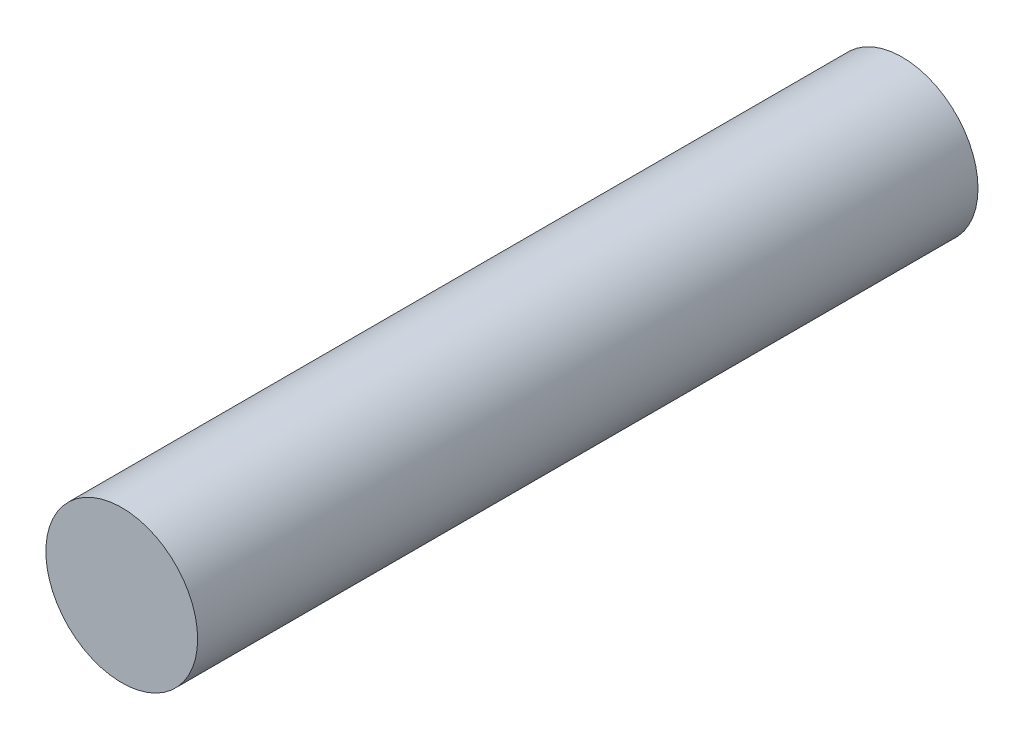
SolidWorks part; units mm, degrees
ref_plane "Plan de face" through (0, 0, 0) normal (0, 0, 1) x (1, 0, 0)
ref_plane "Plan de dessus" through (0, 0, 0) normal (0, 1, 0) x (1, 0, 0)
ref_plane "Plan de droite" through (0, 0, 0) normal (1, 0, 0) x (0, 0, -1)
sketch "Esquisse2" plane through (0, 0, 0) normal (0, 0, 1) x (1, 0, 0)
  circle A0 centre (0, 0) radius 49.403
  dimension "D1" = 98.806
extrude "Boss.-Extru.1" add sketch "Esquisse2" along normal blind 508
